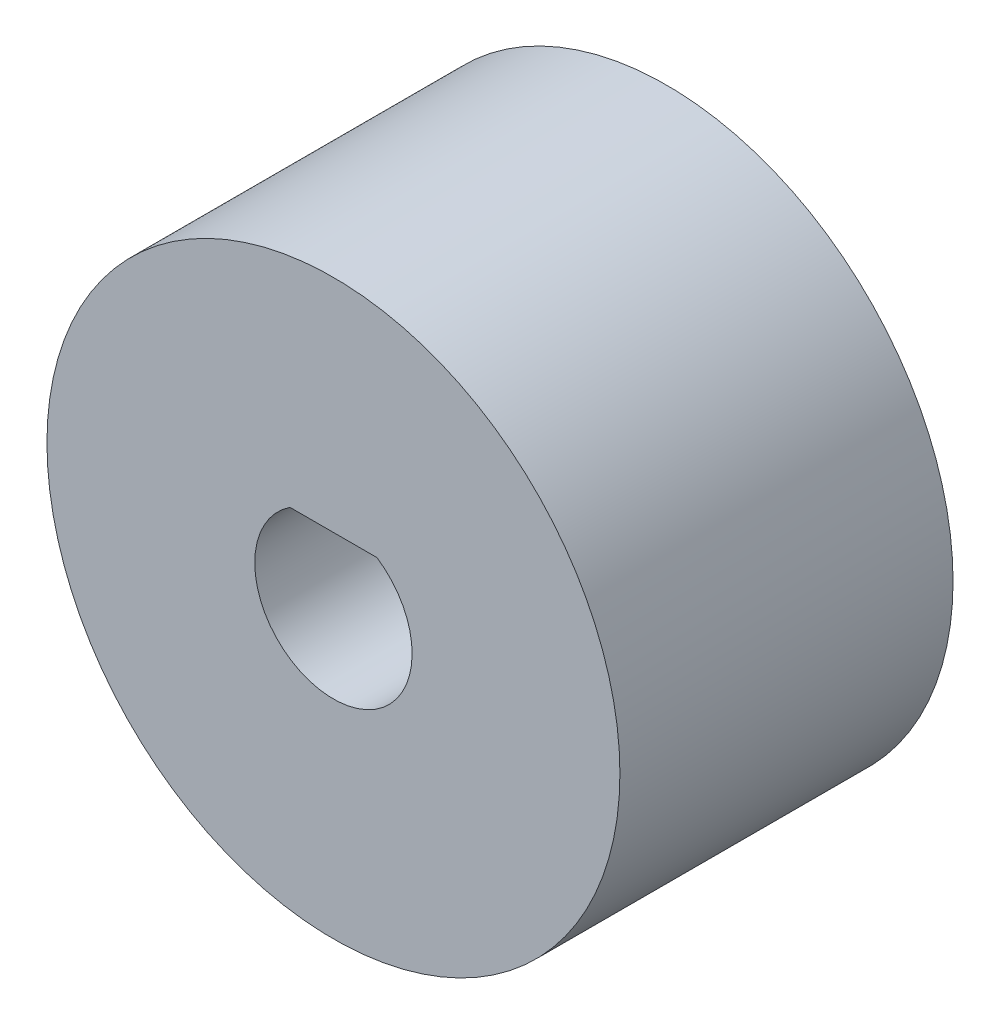
SolidWorks part; units mm, degrees
ref_plane "Front Plane" through (0, 0, 0) normal (0, 0, 1) x (1, 0, 0)
ref_plane "Top Plane" through (0, 0, 0) normal (0, 1, 0) x (1, 0, 0)
ref_plane "Right Plane" through (0, 0, 0) normal (1, 0, 0) x (0, 0, -1)
sketch "Sketch1" plane through (0, 0, 0) normal (0, 0, 1) x (1, 0, 0)
  line L1 (-1.6583, 2.5) -> (1.6583, 2.5)
  circle A0 centre (0, 0) radius 10.922
  arc A1 (-1.6583, 2.5) -> (1.6583, 2.5) centre (0, 0) ccw
  dimension "D1" = 21.844
  dimension "D2" = 6
extrude "Boss-Extrude1" add sketch "Sketch1" along normal blind 12.7
